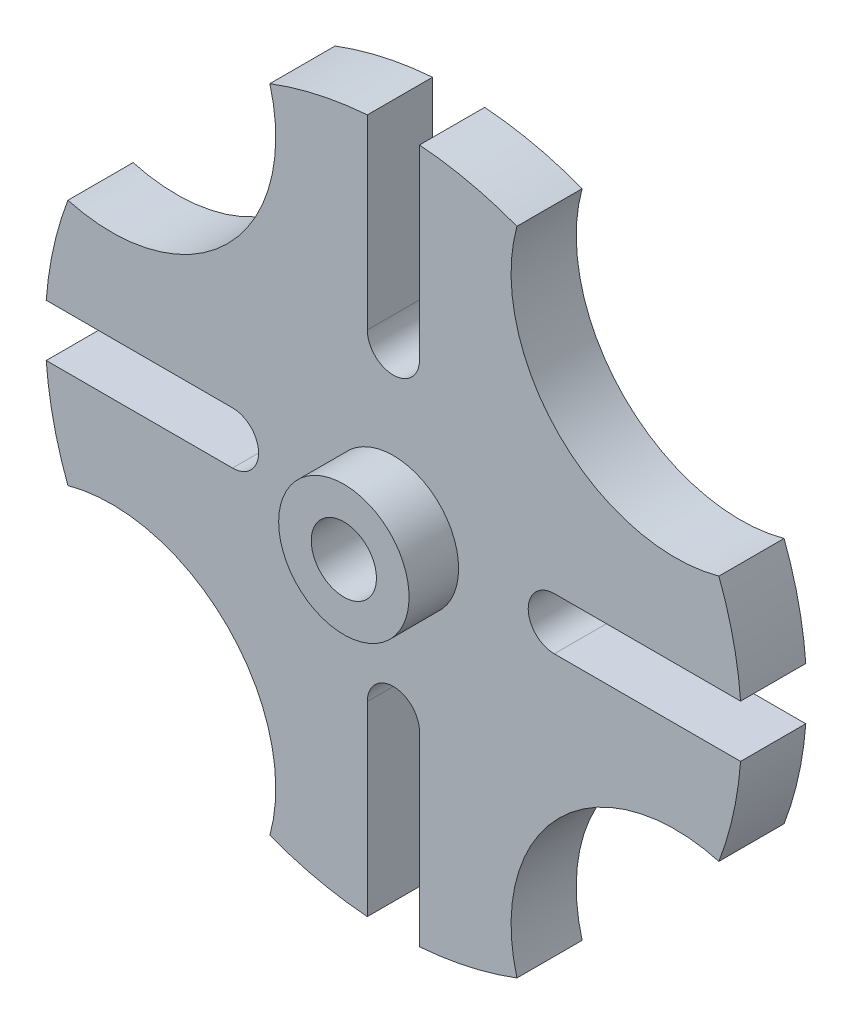
SolidWorks part; units mm, degrees
ref_plane "Front Plane" through (0, 0, 0) normal (0, 0, 1) x (1, 0, 0)
ref_plane "Top Plane" through (0, 0, 0) normal (0, 1, 0) x (1, 0, 0)
ref_plane "Right Plane" through (0, 0, 0) normal (1, 0, 0) x (0, 0, -1)
sketch "Sketch1" plane through (0, 0, 0) normal (0, 0, 1) x (1, 0, 0)
  line L0 (13.1305, 0) -> (33.909, 0) construction
  line L1 (0, 0) -> (27.4616, 27.4616) construction
  line L2 (15.6705, -2.54) -> (33.8137, -2.54)
  line L4 (0, -2.54) -> (63.4961, -2.54) construction
  line L5 (0, 0) -> (63.4961, 0) construction
  line L6 (2.54, -15.6705) -> (2.54, -33.8137)
  line L7 (15.6705, 2.54) -> (33.8137, 2.54)
  line L8 (-2.54, -15.6705) -> (-2.54, -33.8137)
  line L9 (-15.6705, -2.54) -> (-33.8137, -2.54)
  line L10 (-15.6705, 2.54) -> (-33.8137, 2.54)
  line L11 (-2.54, 15.6705) -> (-2.54, 33.8137)
  line L12 (2.54, 15.6705) -> (2.54, 33.8137)
  arc A1 (33.8137, 2.54) -> (31.7026, 12.0318) centre (0, 0) ccw
  circle A2 centre (0, 0) radius 15.875 construction
  arc A6 (15.6705, 2.54) -> (15.6705, -2.54) centre (15.6705, 0) ccw
  arc A7 (12.0318, 31.7026) -> (31.7026, 12.0318) centre (27.4616, 27.4616) ccw
  arc A8 (12.0318, 31.7026) -> (2.54, 33.8137) centre (0, 0) ccw
  arc A9 (31.7026, -12.0318) -> (12.0318, -31.7026) centre (27.4616, -27.4616) ccw
  arc A10 (-12.0318, -31.7026) -> (-31.7026, -12.0318) centre (-27.4616, -27.4616) ccw
  arc A11 (-31.7026, 12.0318) -> (-12.0318, 31.7026) centre (-27.4616, 27.4616) ccw
  arc A12 (31.7026, -12.0318) -> (33.8137, -2.54) centre (0, 0) ccw
  arc A13 (-12.0318, -31.7026) -> (-2.54, -33.8137) centre (0, 0) ccw
  arc A14 (-31.7026, 12.0318) -> (-33.8137, 2.54) centre (0, 0) ccw
  arc A15 (2.54, -15.6705) -> (-2.54, -15.6705) centre (0, -15.6705) ccw
  arc A16 (-15.6705, -2.54) -> (-15.6705, 2.54) centre (-15.6705, 0) ccw
  arc A17 (-2.54, 15.6705) -> (2.54, 15.6705) centre (0, 15.6705) ccw
  arc A18 (2.54, -33.8137) -> (12.0318, -31.7026) centre (0, 0) ccw
  arc A19 (-33.8137, -2.54) -> (-31.7026, -12.0318) centre (0, 0) ccw
  arc A20 (-2.54, 33.8137) -> (-12.0318, 31.7026) centre (0, 0) ccw
  dimension "D2" = 67.818
  dimension "D3" = 31.75
  dimension "D7" = 32.004
  dimension "D1" = 45
  dimension "D6" = 5.08
  dimension "D4" = 38.8366
  dimension "D5" = 2.54
  dimension "D8" = 4
  dimension "D9" = 4
extrude "Boss-Extrude1" add sketch "Sketch1" along normal blind 6.35
sketch "Sketch2" plane through (0, 0, 0) normal (0, 0, -1) x (-1, 0, 0)
  circle A0 centre (0, 0) radius 3.175
  circle A1 centre (0, 0) radius 6.35
  dimension "D1" = 6.35
  dimension "D2" = 12.7
extrude "Boss-Extrude2" add sketch "Sketch2" against normal blind 11.176
sketch "Sketch3" plane through (0, 0, 6.35) normal (0, 0, 1) x (1, 0, 0)
  circle A1 centre (0, 0) radius 3.175
  circle A2 centre (0, 0) radius 3.175
  dimension "D1" = 0
extrude "Cut-Extrude1" cut sketch "Sketch3" against normal through all
equation "\"D7@Sketch1\"=0.63*2"
